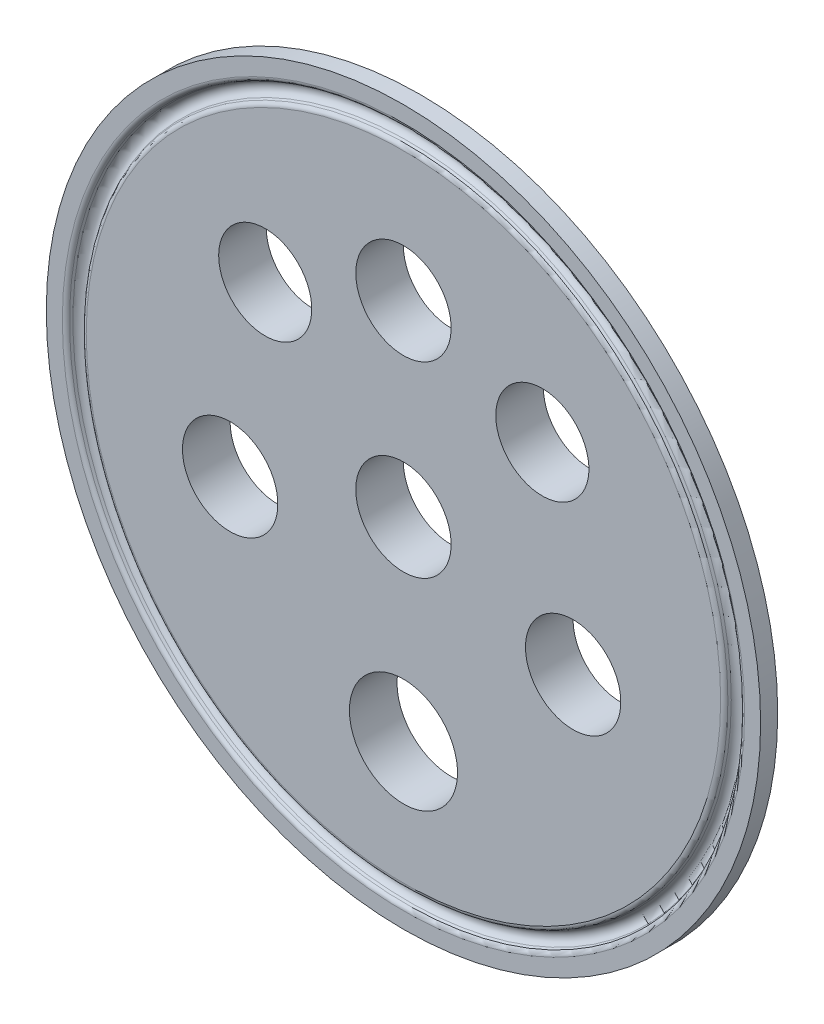
SolidWorks part; units mm, degrees
ref_plane "Front Plane" through (0, 0, 0) normal (0, 0, 1) x (1, 0, 0)
ref_plane "Top Plane" through (0, 0, 0) normal (0, 1, 0) x (1, 0, 0)
ref_plane "Right Plane" through (0, 0, 0) normal (1, 0, 0) x (0, 0, -1)
sketch "Sketch1" plane through (0, 0, 0) normal (1, 0, 0) x (0, 0, -1)
  line L0 (0, 0) -> (7.9248, 0) construction
  line L1 (0, 0) -> (0, 52.8099)
  line L2 (0, 59.4614) -> (2.8448, 59.4614)
  line L3 (2.8448, 59.4614) -> (7.9248, 45.5042)
  line L4 (7.9248, 45.5042) -> (7.9248, 0)
  line L5 (0, 56.7911) -> (0, 59.4614)
  line L6 (0.4797, 56.0663) -> (0.8729, 55.8994)
  line L7 (0.4797, 53.5347) -> (0.8729, 53.7016)
  line L8 (0, 56.2699) -> (0, 53.3311) construction
  line L9 (0, 54.8005) -> (0.4064, 54.8005) construction
  line L10 (0, 0) -> (7.9248, 0)
  arc A0 (0.8729, 53.7016) -> (0.8729, 55.8994) centre (0.4064, 54.8005) ccw
  arc A2 (0, 52.8099) -> (0.4797, 53.5347) centre (0.7874, 52.8099) cw
  arc A3 (0, 56.7911) -> (0.4797, 56.0663) centre (0.7874, 56.7911) ccw
  dimension "K" = 1.1938
  dimension "L" = 0.7874
  dimension "I" = 20
  dimension "C" = 91.0084
  dimension "F" = 2.8448
  dimension "H" = 0.4064
  dimension "B" = 109.601
  dimension "A" = 118.9228
  dimension "M" = 46
  dimension "N" = 23
  dimension "Length" = 7.9248
revolve "Revolve1" add sketch "Sketch1" angle 360 about L0
sketch "Sketch2" plane through (0, 0, -7.9248) normal (0, 0, -1) x (-1, 0, 0)
  circle A8 centre (-23.1214, 22.3296) radius 7.75
  circle A9 centre (23.0149, 22.3296) radius 7.75
  circle A10 centre (0, 31.1981) radius 7.9375
  circle A11 centre (0, 0) radius 7.9375
  circle A12 centre (-28.2481, -8.6142) radius 7.9375
  circle A13 centre (0, -32.3777) radius 9
  circle A14 centre (28.851, -8.6142) radius 7.9375
  circle A15 centre (-28.2481, -8.6142) radius 13.716 construction
  circle A16 centre (28.851, -8.6142) radius 13.716 construction
  point P14 (26.485, -10.6647)
  point P17 (-27.3017, -4.8287)
  point P19 (23.0149, 22.3296)
  point P20 (28.6933, -6.0905)
  point P22 (26.1695, -11.6111)
  point P23 (-28.2481, -8.6142)
  point P24 (0, -32.2741)
  point P25 (28.851, -8.6142)
  point P26 (0, -32.3777)
  dimension "D1" = 15.875
  dimension "D3" = 15.875
  dimension "D4" = 15.875
  dimension "D5" = 15.875
  dimension "D6" = 15.5
  dimension "D7" = 15.5
  dimension "D2" = 27.432
  dimension "D8" = 27.432
  dimension "D9" = 18
extrude "Cut-Extrude1" cut sketch "Sketch2" against normal through all
equation "\"D3@Sketch2\"=\"D1@Sketch2\""
equation "\"D4@Sketch2\"=\"D1@Sketch2\""
equation "\"D5@Sketch2\"=\"D1@Sketch2\""
equation "\"D7@Sketch2\"=\"D6@Sketch2\""
equation "\"D8@Sketch2\"=\"D2@Sketch2\""
